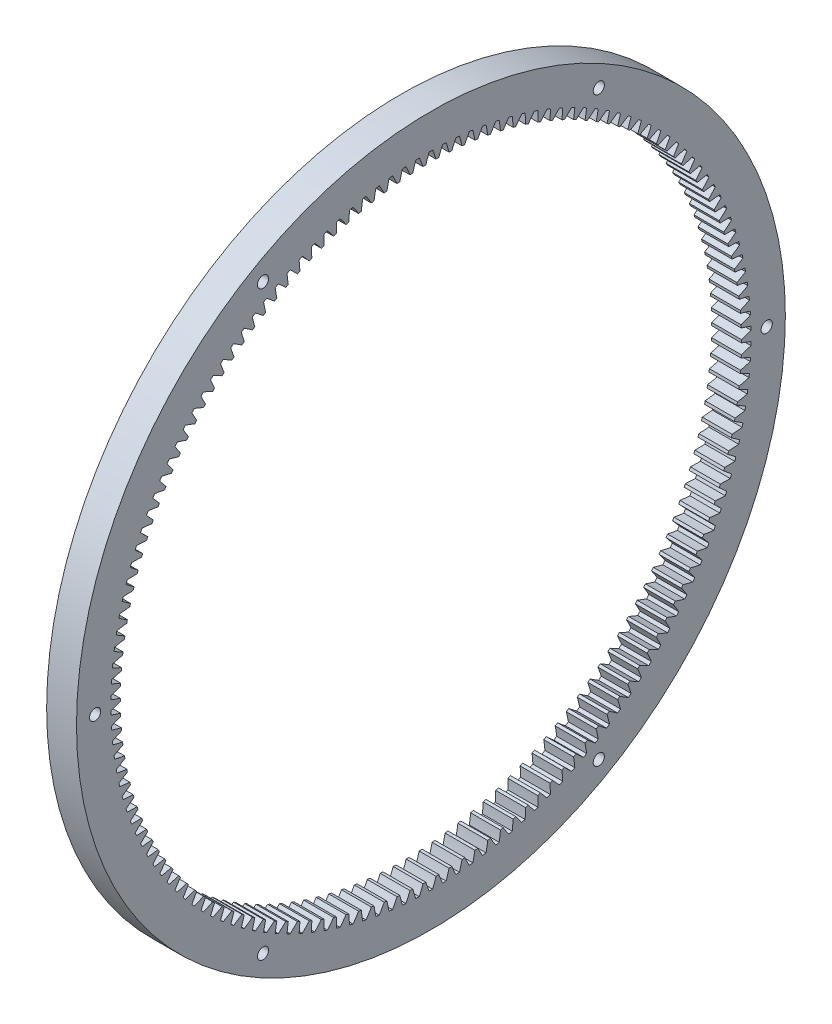
SolidWorks part; units mm, degrees
ref_plane "Plano frontal" through (0, 0, 0) normal (0, 0, 1) x (1, 0, 0)
ref_plane "Plano superior" through (0, 0, 0) normal (0, 1, 0) x (1, 0, 0)
ref_plane "Plano direito" through (0, 0, 0) normal (1, 0, 0) x (0, 0, -1)
ref_plane "Plano1" through (12, 0, 0) normal (1, 0, 0) x (0, 0, -1)
sketch "Esboço1" plane through (12, 0, 0) normal (1, 0, 0) x (0, 0, -1)
  circle A0 centre (-45, 77.9423) radius 1.5
  circle A1 centre (-90, 0) radius 1.5
  circle A2 centre (-45, -77.9423) radius 1.5
  circle A3 centre (45, -77.9423) radius 1.5
  circle A4 centre (90, 0) radius 1.5
  circle A5 centre (45, 77.9423) radius 1.5
  circle A6 centre (0, 0) radius 95
  arc A7 (2.1245, 83.2229) -> (3.1214, 85.7254) centre (41.7952, 68.8695) cw
  arc A8 (3.1214, 85.7254) -> (4.0628, 85.686) centre (0, 0) cw
  arc A9 (4.0628, 85.686) -> (4.8469, 83.1088) centre (-35.8858, 72.1253) cw
  arc A10 (4.8469, 83.1088) -> (5.6077, 83.0609) centre (0, 0) cw
  arc A11 (5.6077, 83.0609) -> (6.7085, 85.5195) centre (44.6425, 67.0589) cw
  arc A12 (6.7085, 85.5195) -> (7.6474, 85.4407) centre (0, 0) cw
  arc A13 (7.6474, 85.4407) -> (8.3228, 82.8329) centre (-32.834, 73.5647) cw
  arc A14 (8.3228, 82.8329) -> (9.081, 82.7532) centre (0, 0) cw
  arc A15 (9.081, 82.7532) -> (10.2838, 85.1636) centre (47.4115, 65.1306) cw
  arc A16 (10.2838, 85.1636) -> (11.2186, 85.0455) centre (0, 0) cw
  arc A17 (11.2186, 85.0455) -> (11.7842, 82.4117) centre (-29.7246, 74.8752) cw
  arc A18 (11.7842, 82.4117) -> (12.5383, 82.3004) centre (0, 0) cw
  arc A19 (12.5383, 82.3004) -> (13.8411, 84.6583) centre (50.0973, 63.0881) cw
  arc A20 (13.8411, 84.6583) -> (14.7701, 84.5011) centre (0, 0) cw
  arc A21 (14.7701, 84.5011) -> (15.2249, 81.846) centre (-26.5631, 76.0542) cw
  arc A22 (15.2249, 81.846) -> (15.9737, 81.7031) centre (0, 0) cw
  arc A23 (15.9737, 81.7031) -> (17.374, 84.0044) centre (52.6952, 60.9349) cw
  arc A24 (17.374, 84.0044) -> (18.2957, 83.8085) centre (0, 0) cw
  arc A25 (18.2957, 83.8085) -> (18.6389, 81.1366) centre (-23.355, 77.0998) cw
  arc A26 (18.6389, 81.1366) -> (19.3811, 80.9626) centre (0, 0) cw
  arc A27 (19.3811, 80.9626) -> (20.8765, 83.2032) centre (55.2006, 58.6748) cw
  arc A28 (20.8765, 83.2032) -> (21.7892, 82.9688) centre (0, 0) cw
  arc A29 (21.7892, 82.9688) -> (22.0202, 80.2849) centre (-20.1059, 78.0102) cw
  arc A30 (22.0202, 80.2849) -> (22.7544, 80.0799) centre (0, 0) cw
  arc A31 (22.7544, 80.0799) -> (24.3424, 82.256) centre (57.6093, 56.3118) cw
  arc A32 (24.3424, 82.256) -> (25.2444, 81.9836) centre (0, 0) cw
  arc A33 (25.2444, 81.9836) -> (25.3629, 79.2924) centre (-16.8215, 78.7837) cw
  arc A34 (25.3629, 79.2924) -> (26.0879, 79.0568) centre (0, 0) cw
  arc A35 (26.0879, 79.0568) -> (27.7656, 81.1644) centre (59.9168, 53.8499) cw
  arc A36 (27.7656, 81.1644) -> (28.6554, 80.8546) centre (0, 0) cw
  arc A37 (28.6554, 80.8546) -> (28.6611, 78.1608) centre (-13.5077, 79.419) cw
  arc A38 (28.6611, 78.1608) -> (29.3756, 77.895) centre (0, 0) cw
  arc A39 (29.3756, 77.895) -> (31.14, 79.9305) centre (62.1193, 51.2936) cw
  arc A40 (31.14, 79.9305) -> (32.0161, 79.5837) centre (0, 0) cw
  arc A41 (32.0161, 79.5837) -> (31.909, 76.892) centre (-10.1701, 79.915) cw
  arc A42 (31.909, 76.892) -> (32.6117, 76.5966) centre (0, 0) cw
  arc A43 (32.6117, 76.5966) -> (34.4599, 78.5564) centre (64.2127, 48.6474) cw
  arc A44 (34.4599, 78.5564) -> (35.3207, 78.1732) centre (0, 0) cw
  arc A45 (35.3207, 78.1732) -> (35.1009, 75.4883) centre (-6.8147, 80.2708) cw
  arc A46 (35.1009, 75.4883) -> (35.7906, 75.1638) centre (0, 0) cw
  arc A47 (35.7906, 75.1638) -> (37.7192, 77.0445) centre (66.1936, 45.9157) cw
  arc A48 (37.7192, 77.0445) -> (38.5632, 76.6255) centre (0, 0) cw
  arc A49 (38.5632, 76.6255) -> (38.2312, 73.9523) centre (-3.4473, 80.4858) cw
  arc A50 (38.2312, 73.9523) -> (38.9068, 73.5991) centre (0, 0) cw
  arc A51 (38.9068, 73.5991) -> (40.9124, 75.3974) centre (68.0582, 43.1036) cw
  arc A52 (40.9124, 75.3974) -> (41.7381, 74.9435) centre (0, 0) cw
  arc A53 (41.7381, 74.9435) -> (41.2945, 72.2864) centre (-0.0739, 80.5595) cw
  arc A54 (41.2945, 72.2864) -> (41.9546, 71.9053) centre (0, 0) cw
  arc A55 (41.9546, 71.9053) -> (44.0339, 73.618) centre (69.8035, 40.2158) cw
  arc A56 (44.0339, 73.618) -> (44.8398, 73.1299) centre (0, 0) cw
  arc A57 (44.8398, 73.1299) -> (44.2853, 70.4938) centre (3.2997, 80.492) cw
  arc A58 (44.2853, 70.4938) -> (44.9289, 70.0853) centre (0, 0) cw
  arc A59 (44.9289, 70.0853) -> (47.078, 71.7095) centre (71.4264, 37.2574) cw
  arc A60 (47.078, 71.7095) -> (47.8629, 71.1881) centre (0, 0) cw
  arc A61 (47.8629, 71.1881) -> (47.1984, 68.5775) centre (6.6674, 80.2832) cw
  arc A62 (47.1984, 68.5775) -> (47.8244, 68.1424) centre (0, 0) cw
  arc A63 (47.8244, 68.1424) -> (50.0396, 69.6752) centre (72.9239, 34.2337) cw
  arc A64 (50.0396, 69.6752) -> (50.8019, 69.1213) centre (0, 0) cw
  arc A65 (50.8019, 69.1213) -> (50.0288, 66.5409) centre (10.0235, 79.9335) cw
  arc A66 (50.0288, 66.5409) -> (50.6359, 66.08) centre (0, 0) cw
  arc A67 (50.6359, 66.08) -> (52.9134, 67.5186) centre (74.2935, 31.15) cw
  arc A68 (52.9134, 67.5186) -> (53.6519, 66.9333) centre (0, 0) cw
  arc A69 (53.6519, 66.9333) -> (52.7713, 64.3875) centre (13.362, 79.4437) cw
  arc A70 (52.7713, 64.3875) -> (53.3587, 63.9016) centre (0, 0) cw
  arc A71 (53.3587, 63.9016) -> (55.6944, 65.2436) centre (75.5327, 28.0116) cw
  arc A72 (55.6944, 65.2436) -> (56.4077, 64.6279) centre (0, 0) cw
  arc A73 (56.4077, 64.6279) -> (55.4213, 62.1212) centre (16.677, 78.8145) cw
  arc A74 (55.4213, 62.1212) -> (55.9878, 61.6111) centre (0, 0) cw
  arc A75 (55.9878, 61.6111) -> (58.3777, 62.8541) centre (76.6395, 24.824) cw
  arc A76 (58.3777, 62.8541) -> (59.0645, 62.2091) centre (0, 0) cw
  arc A77 (59.0645, 62.2091) -> (57.974, 59.7459) centre (19.9628, 78.047) cw
  arc A78 (57.974, 59.7459) -> (58.5187, 59.2126) centre (0, 0) cw
  arc A79 (58.5187, 59.2126) -> (60.9585, 60.3544) centre (77.6118, 21.5929) cw
  arc A80 (60.9585, 60.3544) -> (61.6178, 59.6812) centre (0, 0) cw
  arc A81 (61.6178, 59.6812) -> (60.4251, 57.2658) centre (23.2135, 77.1426) cw
  arc A82 (60.4251, 57.2658) -> (60.9469, 56.7101) centre (0, 0) cw
  arc A83 (60.9469, 56.7101) -> (63.4324, 57.7488) centre (78.4479, 18.3239) cw
  arc A84 (63.4324, 57.7488) -> (64.0629, 57.0486) centre (0, 0) cw
  arc A85 (64.0629, 57.0486) -> (62.7701, 54.6852) centre (26.4236, 76.1028) cw
  arc A86 (62.7701, 54.6852) -> (63.2682, 54.1082) centre (0, 0) cw
  arc A87 (63.2682, 54.1082) -> (65.7951, 55.0418) centre (79.1464, 15.0228) cw
  arc A88 (65.7951, 55.0418) -> (66.3957, 54.3158) centre (0, 0) cw
  arc A89 (66.3957, 54.3158) -> (65.005, 52.0087) centre (29.5872, 74.9295) cw
  arc A90 (65.005, 52.0087) -> (65.4785, 51.4113) centre (0, 0) cw
  arc A91 (65.4785, 51.4113) -> (68.0423, 52.2384) centre (79.7061, 11.6953) cw
  arc A92 (68.0423, 52.2384) -> (68.6119, 51.4878) centre (0, 0) cw
  arc A93 (68.6119, 51.4878) -> (67.1259, 49.241) centre (32.699, 73.6248) cw
  arc A94 (67.1259, 49.241) -> (67.574, 48.6243) centre (0, 0) cw
  arc A95 (67.574, 48.6243) -> (70.1701, 49.3432) centre (80.1259, 8.3473) cw
  arc A96 (70.1701, 49.3432) -> (70.7078, 48.5695) centre (0, 0) cw
  arc A97 (70.7078, 48.5695) -> (69.129, 46.3868) centre (35.7534, 72.191) cw
  arc A98 (69.129, 46.3868) -> (69.5509, 45.7519) centre (0, 0) cw
  arc A99 (69.5509, 45.7519) -> (72.1748, 46.3615) centre (80.4052, 4.9846) cw
  arc A100 (72.1748, 46.3615) -> (72.6797, 45.566) centre (0, 0) cw
  arc A101 (72.6797, 45.566) -> (71.0109, 43.4513) centre (38.7451, 70.6304) cw
  arc A102 (71.0109, 43.4513) -> (71.4058, 42.7993) centre (0, 0) cw
  arc A103 (71.4058, 42.7993) -> (74.0529, 43.2985) centre (80.5434, 1.6132) cw
  arc A104 (74.0529, 43.2985) -> (74.524, 42.4825) centre (0, 0) cw
  arc A105 (74.524, 42.4825) -> (72.7681, 40.4396) centre (41.6688, 68.946) cw
  arc A106 (72.7681, 40.4396) -> (73.1354, 39.7716) centre (0, 0) cw
  arc A107 (73.1354, 39.7716) -> (75.8011, 40.1595) centre (80.5403, -1.761) cw
  arc A108 (75.8011, 40.1595) -> (76.2377, 39.3245) centre (0, 0) cw
  arc A109 (76.2377, 39.3245) -> (74.3977, 37.3569) centre (44.5194, 67.1406) cw
  arc A110 (74.3977, 37.3569) -> (74.7367, 36.6741) centre (0, 0) cw
  arc A111 (74.7367, 36.6741) -> (77.4163, 36.95) centre (80.3959, -5.1321) cw
  arc A112 (77.4163, 36.95) -> (77.8175, 36.0975) centre (0, 0) cw
  arc A113 (77.8175, 36.0975) -> (75.8968, 34.2087) centre (47.2919, 65.2174) cw
  arc A114 (75.8968, 34.2087) -> (76.2069, 33.5123) centre (0, 0) cw
  arc A115 (76.2069, 33.5123) -> (78.8957, 33.6758) centre (80.1105, -8.4942) cw
  arc A116 (78.8957, 33.6758) -> (79.2609, 32.8071) centre (0, 0) cw
  arc A117 (79.2609, 32.8071) -> (77.2628, 31.0004) centre (49.9815, 63.1799) cw
  arc A118 (77.2628, 31.0004) -> (77.5434, 30.2917) centre (0, 0) cw
  arc A119 (77.5434, 30.2917) -> (80.2367, 30.3424) centre (79.6845, -11.8415) cw
  arc A120 (80.2367, 30.3424) -> (80.5652, 29.4593) centre (0, 0) cw
  arc A121 (80.5652, 29.4593) -> (78.4932, 27.7378) centre (52.5833, 61.0314) cw
  arc A122 (78.4932, 27.7378) -> (78.7439, 27.0179) centre (0, 0) cw
  arc A123 (78.7439, 27.0179) -> (81.437, 26.9558) centre (79.1187, -15.1679) cw
  arc A124 (81.437, 26.9558) -> (81.7281, 26.0597) centre (0, 0) cw
  arc A125 (81.7281, 26.0597) -> (79.5858, 24.4265) centre (55.0929, 58.7759) cw
  arc A126 (79.5858, 24.4265) -> (79.8062, 23.6968) centre (0, 0) cw
  arc A127 (79.8062, 23.6968) -> (82.4943, 23.522) centre (78.4142, -18.4678) cw
  arc A128 (82.4943, 23.522) -> (82.7477, 22.6144) centre (0, 0) cw
  arc A129 (82.7477, 22.6144) -> (80.5389, 21.0724) centre (57.5059, 56.4173) cw
  arc A130 (80.5389, 21.0724) -> (80.7285, 20.334) centre (0, 0) cw
  arc A131 (80.7285, 20.334) -> (83.4069, 20.0468) centre (77.572, -21.7352) cw
  arc A132 (83.4069, 20.0468) -> (83.6221, 19.1295) centre (0, 0) cw
  arc A133 (83.6221, 19.1295) -> (81.3507, 17.6813) centre (59.818, 53.9597) cw
  arc A134 (81.3507, 17.6813) -> (81.5092, 16.9356) centre (0, 0) cw
  arc A135 (81.5092, 16.9356) -> (84.1733, 16.5365) centre (76.5938, -24.9645) cw
  arc A136 (84.1733, 16.5365) -> (84.3498, 15.611) centre (0, 0) cw
  arc A137 (84.3498, 15.611) -> (82.0197, 14.2592) centre (62.0251, 51.4075) cw
  arc A138 (82.0197, 14.2592) -> (82.1469, 13.5075) centre (0, 0) cw
  arc A139 (82.1469, 13.5075) -> (84.7919, 12.9972) centre (75.4812, -28.15) cw
  arc A140 (84.7919, 12.9972) -> (84.9295, 12.0651) centre (0, 0) cw
  arc A141 (84.9295, 12.0651) -> (82.5449, 10.812) centre (64.1234, 48.7651) cw
  arc A142 (82.5449, 10.812) -> (82.6405, 10.0557) centre (0, 0) cw
  arc A143 (82.6405, 10.0557) -> (85.2618, 9.4351) centre (74.2362, -31.2862) cw
  arc A144 (85.2618, 9.4351) -> (85.3603, 8.498) centre (0, 0) cw
  arc A145 (85.3603, 8.498) -> (82.9253, 7.3459) centre (66.1092, 46.0371) cw
  arc A146 (82.9253, 7.3459) -> (82.9891, 6.5863) centre (0, 0) cw
  arc A147 (82.9891, 6.5863) -> (85.5821, 5.8564) centre (72.861, -34.3674) cw
  arc A148 (85.5821, 5.8564) -> (85.6413, 4.916) centre (0, 0) cw
  arc A149 (85.6413, 4.916) -> (83.1601, 3.8669) centre (67.9791, 43.2283) cw
  arc A150 (83.1601, 3.8669) -> (83.1921, 3.1053) centre (0, 0) cw
  arc A151 (83.1921, 3.1053) -> (85.7523, 2.2675) centre (71.3579, -37.3884) cw
  arc A152 (85.7523, 2.2675) -> (85.772, 1.3254) centre (0, 0) cw
  arc A153 (85.772, 1.3254) -> (83.2491, 0.3811) centre (69.7297, 40.3437) cw
  arc A154 (83.2491, 0.3811) -> (83.2491, -0.3811) centre (0, 0) cw
  arc A155 (83.2491, -0.3811) -> (85.772, -1.3254) centre (69.7297, -40.3437) cw
  arc A156 (85.772, -1.3254) -> (85.7523, -2.2675) centre (0, 0) cw
  arc A157 (85.7523, -2.2675) -> (83.1921, -3.1053) centre (71.3579, 37.3884) cw
  arc A158 (83.1921, -3.1053) -> (83.1601, -3.8669) centre (0, 0) cw
  arc A159 (83.1601, -3.8669) -> (85.6413, -4.916) centre (67.9791, -43.2283) cw
  arc A160 (85.6413, -4.916) -> (85.5821, -5.8564) centre (0, 0) cw
  arc A161 (85.5821, -5.8564) -> (82.9891, -6.5863) centre (72.861, 34.3674) cw
  arc A162 (82.9891, -6.5863) -> (82.9253, -7.3459) centre (0, 0) cw
  arc A163 (82.9253, -7.3459) -> (85.3603, -8.498) centre (66.1092, -46.0371) cw
  arc A164 (85.3603, -8.498) -> (85.2618, -9.4351) centre (0, 0) cw
  arc A165 (85.2618, -9.4351) -> (82.6405, -10.0557) centre (74.2362, 31.2862) cw
  arc A166 (82.6405, -10.0557) -> (82.5449, -10.812) centre (0, 0) cw
  arc A167 (82.5449, -10.812) -> (84.9295, -12.0651) centre (64.1234, -48.7651) cw
  arc A168 (84.9295, -12.0651) -> (84.7919, -12.9972) centre (0, 0) cw
  arc A169 (84.7919, -12.9972) -> (82.1469, -13.5075) centre (75.4812, 28.15) cw
  arc A170 (82.1469, -13.5075) -> (82.0197, -14.2592) centre (0, 0) cw
  arc A171 (82.0197, -14.2592) -> (84.3498, -15.611) centre (62.0251, -51.4075) cw
  arc A172 (84.3498, -15.611) -> (84.1733, -16.5365) centre (0, 0) cw
  arc A173 (84.1733, -16.5365) -> (81.5092, -16.9356) centre (76.5938, 24.9645) cw
  arc A174 (81.5092, -16.9356) -> (81.3507, -17.6813) centre (0, 0) cw
  arc A175 (81.3507, -17.6813) -> (83.6221, -19.1295) centre (59.818, -53.9597) cw
  arc A176 (83.6221, -19.1295) -> (83.4069, -20.0468) centre (0, 0) cw
  arc A177 (83.4069, -20.0468) -> (80.7285, -20.334) centre (77.572, 21.7352) cw
  arc A178 (80.7285, -20.334) -> (80.5389, -21.0724) centre (0, 0) cw
  arc A179 (80.5389, -21.0724) -> (82.7477, -22.6144) centre (57.5059, -56.4173) cw
  arc A180 (82.7477, -22.6144) -> (82.4943, -23.522) centre (0, 0) cw
  arc A181 (82.4943, -23.522) -> (79.8062, -23.6968) centre (78.4142, 18.4678) cw
  arc A182 (79.8062, -23.6968) -> (79.5858, -24.4265) centre (0, 0) cw
  arc A183 (79.5858, -24.4265) -> (81.7281, -26.0597) centre (55.0929, -58.7759) cw
  arc A184 (81.7281, -26.0597) -> (81.437, -26.9558) centre (0, 0) cw
  arc A185 (81.437, -26.9558) -> (78.7439, -27.0179) centre (79.1187, 15.1679) cw
  arc A186 (78.7439, -27.0179) -> (78.4932, -27.7378) centre (0, 0) cw
  arc A187 (78.4932, -27.7378) -> (80.5652, -29.4593) centre (52.5833, -61.0314) cw
  arc A188 (80.5652, -29.4593) -> (80.2367, -30.3424) centre (0, 0) cw
  arc A189 (80.2367, -30.3424) -> (77.5434, -30.2917) centre (79.6845, 11.8415) cw
  arc A190 (77.5434, -30.2917) -> (77.2628, -31.0004) centre (0, 0) cw
  arc A191 (77.2628, -31.0004) -> (79.2609, -32.8071) centre (49.9815, -63.1799) cw
  arc A192 (79.2609, -32.8071) -> (78.8957, -33.6758) centre (0, 0) cw
  arc A193 (78.8957, -33.6758) -> (76.2069, -33.5123) centre (80.1105, 8.4942) cw
  arc A194 (76.2069, -33.5123) -> (75.8968, -34.2087) centre (0, 0) cw
  arc A195 (75.8968, -34.2087) -> (77.8175, -36.0975) centre (47.2919, -65.2174) cw
  arc A196 (77.8175, -36.0975) -> (77.4163, -36.95) centre (0, 0) cw
  arc A197 (77.4163, -36.95) -> (74.7367, -36.6741) centre (80.3959, 5.1321) cw
  arc A198 (74.7367, -36.6741) -> (74.3977, -37.3569) centre (0, 0) cw
  arc A199 (74.3977, -37.3569) -> (76.2377, -39.3245) centre (44.5194, -67.1406) cw
  arc A200 (76.2377, -39.3245) -> (75.8011, -40.1595) centre (0, 0) cw
  arc A201 (75.8011, -40.1595) -> (73.1354, -39.7716) centre (80.5403, 1.761) cw
  arc A202 (73.1354, -39.7716) -> (72.7681, -40.4396) centre (0, 0) cw
  arc A203 (72.7681, -40.4396) -> (74.524, -42.4825) centre (41.6688, -68.946) cw
  arc A204 (74.524, -42.4825) -> (74.0529, -43.2985) centre (0, 0) cw
  arc A205 (74.0529, -43.2985) -> (71.4058, -42.7993) centre (80.5434, -1.6132) cw
  arc A206 (71.4058, -42.7993) -> (71.0109, -43.4513) centre (0, 0) cw
  arc A207 (71.0109, -43.4513) -> (72.6797, -45.566) centre (38.7451, -70.6304) cw
  arc A208 (72.6797, -45.566) -> (72.1748, -46.3615) centre (0, 0) cw
  arc A209 (72.1748, -46.3615) -> (69.5509, -45.7519) centre (80.4052, -4.9846) cw
  arc A210 (69.5509, -45.7519) -> (69.129, -46.3868) centre (0, 0) cw
  arc A211 (69.129, -46.3868) -> (70.7078, -48.5695) centre (35.7534, -72.191) cw
  arc A212 (70.7078, -48.5695) -> (70.1701, -49.3432) centre (0, 0) cw
  arc A213 (70.1701, -49.3432) -> (67.574, -48.6243) centre (80.1259, -8.3473) cw
  arc A214 (67.574, -48.6243) -> (67.1259, -49.241) centre (0, 0) cw
  arc A215 (67.1259, -49.241) -> (68.6119, -51.4878) centre (32.699, -73.6248) cw
  arc A216 (68.6119, -51.4878) -> (68.0423, -52.2384) centre (0, 0) cw
  arc A217 (68.0423, -52.2384) -> (65.4785, -51.4113) centre (79.7061, -11.6953) cw
  arc A218 (65.4785, -51.4113) -> (65.005, -52.0087) centre (0, 0) cw
  arc A219 (65.005, -52.0087) -> (66.3957, -54.3158) centre (29.5872, -74.9295) cw
  arc A220 (66.3957, -54.3158) -> (65.7951, -55.0418) centre (0, 0) cw
  arc A221 (65.7951, -55.0418) -> (63.2682, -54.1082) centre (79.1464, -15.0228) cw
  arc A222 (63.2682, -54.1082) -> (62.7701, -54.6852) centre (0, 0) cw
  arc A223 (62.7701, -54.6852) -> (64.0629, -57.0486) centre (26.4236, -76.1028) cw
  arc A224 (64.0629, -57.0486) -> (63.4324, -57.7488) centre (0, 0) cw
  arc A225 (63.4324, -57.7488) -> (60.9469, -56.7101) centre (78.4479, -18.3239) cw
  arc A226 (60.9469, -56.7101) -> (60.4251, -57.2658) centre (0, 0) cw
  arc A227 (60.4251, -57.2658) -> (61.6178, -59.6812) centre (23.2135, -77.1426) cw
  arc A228 (61.6178, -59.6812) -> (60.9585, -60.3544) centre (0, 0) cw
  arc A229 (60.9585, -60.3544) -> (58.5187, -59.2126) centre (77.6118, -21.5929) cw
  arc A230 (58.5187, -59.2126) -> (57.974, -59.7459) centre (0, 0) cw
  arc A231 (57.974, -59.7459) -> (59.0645, -62.2091) centre (19.9628, -78.047) cw
  arc A232 (59.0645, -62.2091) -> (58.3777, -62.8541) centre (0, 0) cw
  arc A233 (58.3777, -62.8541) -> (55.9878, -61.6111) centre (76.6395, -24.824) cw
  arc A234 (55.9878, -61.6111) -> (55.4213, -62.1212) centre (0, 0) cw
  arc A235 (55.4213, -62.1212) -> (56.4077, -64.6279) centre (16.677, -78.8145) cw
  arc A236 (56.4077, -64.6279) -> (55.6944, -65.2436) centre (0, 0) cw
  arc A237 (55.6944, -65.2436) -> (53.3587, -63.9016) centre (75.5327, -28.0116) cw
  arc A238 (53.3587, -63.9016) -> (52.7713, -64.3875) centre (0, 0) cw
  arc A239 (52.7713, -64.3875) -> (53.6519, -66.9333) centre (13.362, -79.4437) cw
  arc A240 (53.6519, -66.9333) -> (52.9134, -67.5186) centre (0, 0) cw
  arc A241 (52.9134, -67.5186) -> (50.6359, -66.08) centre (74.2935, -31.15) cw
  arc A242 (50.6359, -66.08) -> (50.0288, -66.5409) centre (0, 0) cw
  arc A243 (50.0288, -66.5409) -> (50.8019, -69.1213) centre (10.0235, -79.9335) cw
  arc A244 (50.8019, -69.1213) -> (50.0396, -69.6752) centre (0, 0) cw
  arc A245 (50.0396, -69.6752) -> (47.8244, -68.1424) centre (72.9239, -34.2337) cw
  arc A246 (47.8244, -68.1424) -> (47.1984, -68.5775) centre (0, 0) cw
  arc A247 (47.1984, -68.5775) -> (47.8629, -71.1881) centre (6.6674, -80.2832) cw
  arc A248 (47.8629, -71.1881) -> (47.078, -71.7095) centre (0, 0) cw
  arc A249 (47.078, -71.7095) -> (44.9289, -70.0853) centre (71.4264, -37.2574) cw
  arc A250 (44.9289, -70.0853) -> (44.2853, -70.4938) centre (0, 0) cw
  arc A251 (44.2853, -70.4938) -> (44.8398, -73.1299) centre (3.2997, -80.492) cw
  arc A252 (44.8398, -73.1299) -> (44.0339, -73.618) centre (0, 0) cw
  arc A253 (44.0339, -73.618) -> (41.9546, -71.9053) centre (69.8035, -40.2158) cw
  arc A254 (41.9546, -71.9053) -> (41.2945, -72.2864) centre (0, 0) cw
  arc A255 (41.2945, -72.2864) -> (41.7381, -74.9435) centre (-0.0739, -80.5595) cw
  arc A256 (41.7381, -74.9435) -> (40.9124, -75.3974) centre (0, 0) cw
  arc A257 (40.9124, -75.3974) -> (38.9068, -73.5991) centre (68.0582, -43.1036) cw
  arc A258 (38.9068, -73.5991) -> (38.2312, -73.9523) centre (0, 0) cw
  arc A259 (38.2312, -73.9523) -> (38.5632, -76.6255) centre (-3.4473, -80.4858) cw
  arc A260 (38.5632, -76.6255) -> (37.7192, -77.0445) centre (0, 0) cw
  arc A261 (37.7192, -77.0445) -> (35.7906, -75.1638) centre (66.1936, -45.9157) cw
  arc A262 (35.7906, -75.1638) -> (35.1009, -75.4883) centre (0, 0) cw
  arc A263 (35.1009, -75.4883) -> (35.3207, -78.1732) centre (-6.8147, -80.2708) cw
  arc A264 (35.3207, -78.1732) -> (34.4599, -78.5564) centre (0, 0) cw
  arc A265 (34.4599, -78.5564) -> (32.6117, -76.5966) centre (64.2127, -48.6474) cw
  arc A266 (32.6117, -76.5966) -> (31.909, -76.892) centre (0, 0) cw
  arc A267 (31.909, -76.892) -> (32.0161, -79.5837) centre (-10.1701, -79.915) cw
  arc A268 (32.0161, -79.5837) -> (31.14, -79.9305) centre (0, 0) cw
  arc A269 (31.14, -79.9305) -> (29.3756, -77.895) centre (62.1193, -51.2936) cw
  arc A270 (29.3756, -77.895) -> (28.6611, -78.1608) centre (0, 0) cw
  arc A271 (28.6611, -78.1608) -> (28.6554, -80.8546) centre (-13.5077, -79.419) cw
  arc A272 (28.6554, -80.8546) -> (27.7656, -81.1644) centre (0, 0) cw
  arc A273 (27.7656, -81.1644) -> (26.0879, -79.0568) centre (59.9168, -53.8499) cw
  arc A274 (26.0879, -79.0568) -> (25.3629, -79.2924) centre (0, 0) cw
  arc A275 (25.3629, -79.2924) -> (25.2444, -81.9836) centre (-16.8215, -78.7837) cw
  arc A276 (25.2444, -81.9836) -> (24.3424, -82.256) centre (0, 0) cw
  arc A277 (24.3424, -82.256) -> (22.7544, -80.0799) centre (57.6093, -56.3118) cw
  arc A278 (22.7544, -80.0799) -> (22.0202, -80.2849) centre (0, 0) cw
  arc A279 (22.0202, -80.2849) -> (21.7892, -82.9688) centre (-20.1059, -78.0102) cw
  arc A280 (21.7892, -82.9688) -> (20.8765, -83.2032) centre (0, 0) cw
  arc A281 (20.8765, -83.2032) -> (19.3811, -80.9626) centre (55.2006, -58.6748) cw
  arc A282 (19.3811, -80.9626) -> (18.6389, -81.1366) centre (0, 0) cw
  arc A283 (18.6389, -81.1366) -> (18.2957, -83.8085) centre (-23.355, -77.0998) cw
  arc A284 (18.2957, -83.8085) -> (17.374, -84.0044) centre (0, 0) cw
  arc A285 (17.374, -84.0044) -> (15.9737, -81.7031) centre (52.6952, -60.9349) cw
  arc A286 (15.9737, -81.7031) -> (15.2249, -81.846) centre (0, 0) cw
  arc A287 (15.2249, -81.846) -> (14.7701, -84.5011) centre (-26.5631, -76.0542) cw
  arc A288 (14.7701, -84.5011) -> (13.8411, -84.6583) centre (0, 0) cw
  arc A289 (13.8411, -84.6583) -> (12.5383, -82.3004) centre (50.0973, -63.0881) cw
  arc A290 (12.5383, -82.3004) -> (11.7842, -82.4117) centre (0, 0) cw
  arc A291 (11.7842, -82.4117) -> (11.2186, -85.0455) centre (-29.7246, -74.8752) cw
  arc A292 (11.2186, -85.0455) -> (10.2838, -85.1636) centre (0, 0) cw
  arc A293 (10.2838, -85.1636) -> (9.081, -82.7532) centre (47.4115, -65.1306) cw
  arc A294 (9.081, -82.7532) -> (8.3228, -82.8329) centre (0, 0) cw
  arc A295 (8.3228, -82.8329) -> (7.6474, -85.4407) centre (-32.834, -73.5647) cw
  arc A296 (7.6474, -85.4407) -> (6.7085, -85.5195) centre (0, 0) cw
  arc A297 (6.7085, -85.5195) -> (5.6077, -83.0609) centre (44.6425, -67.0589) cw
  arc A298 (5.6077, -83.0609) -> (4.8469, -83.1088) centre (0, 0) cw
  arc A299 (4.8469, -83.1088) -> (4.0628, -85.686) centre (-35.8858, -72.1253) cw
  arc A300 (4.0628, -85.686) -> (3.1214, -85.7254) centre (0, 0) cw
  arc A301 (3.1214, -85.7254) -> (2.1245, -83.2229) centre (41.7952, -68.8695) cw
  arc A302 (2.1245, -83.2229) -> (1.3624, -83.2389) centre (0, 0) cw
  arc A303 (1.3624, -83.2389) -> (0.4711, -85.781) centre (-38.8746, -70.5593) cw
  arc A304 (0.4711, -85.781) -> (-0.4711, -85.781) centre (0, 0) cw
  arc A305 (-0.4711, -85.781) -> (-1.3624, -83.2389) centre (38.8746, -70.5593) cw
  arc A306 (-1.3624, -83.2389) -> (-2.1245, -83.2229) centre (0, 0) cw
  arc A307 (-2.1245, -83.2229) -> (-3.1214, -85.7254) centre (-41.7952, -68.8695) cw
  arc A308 (-3.1214, -85.7254) -> (-4.0628, -85.686) centre (0, 0) cw
  arc A309 (-4.0628, -85.686) -> (-4.8469, -83.1088) centre (35.8858, -72.1253) cw
  arc A310 (-4.8469, -83.1088) -> (-5.6077, -83.0609) centre (0, 0) cw
  arc A311 (-5.6077, -83.0609) -> (-6.7085, -85.5195) centre (-44.6425, -67.0589) cw
  arc A312 (-6.7085, -85.5195) -> (-7.6474, -85.4407) centre (0, 0) cw
  arc A313 (-7.6474, -85.4407) -> (-8.3228, -82.8329) centre (32.834, -73.5647) cw
  arc A314 (-8.3228, -82.8329) -> (-9.081, -82.7532) centre (0, 0) cw
  arc A315 (-9.081, -82.7532) -> (-10.2838, -85.1636) centre (-47.4115, -65.1306) cw
  arc A316 (-10.2838, -85.1636) -> (-11.2186, -85.0455) centre (0, 0) cw
  arc A317 (-11.2186, -85.0455) -> (-11.7842, -82.4117) centre (29.7246, -74.8752) cw
  arc A318 (-11.7842, -82.4117) -> (-12.5383, -82.3004) centre (0, 0) cw
  arc A319 (-12.5383, -82.3004) -> (-13.8411, -84.6583) centre (-50.0973, -63.0881) cw
  arc A320 (-13.8411, -84.6583) -> (-14.7701, -84.5011) centre (0, 0) cw
  arc A321 (-14.7701, -84.5011) -> (-15.2249, -81.846) centre (26.5631, -76.0542) cw
  arc A322 (-15.2249, -81.846) -> (-15.9737, -81.7031) centre (0, 0) cw
  arc A323 (-15.9737, -81.7031) -> (-17.374, -84.0044) centre (-52.6952, -60.9349) cw
  arc A324 (-17.374, -84.0044) -> (-18.2957, -83.8085) centre (0, 0) cw
  arc A325 (-18.2957, -83.8085) -> (-18.6389, -81.1366) centre (23.355, -77.0998) cw
  arc A326 (-18.6389, -81.1366) -> (-19.3811, -80.9626) centre (0, 0) cw
  arc A327 (-19.3811, -80.9626) -> (-20.8765, -83.2032) centre (-55.2006, -58.6748) cw
  arc A328 (-20.8765, -83.2032) -> (-21.7892, -82.9688) centre (0, 0) cw
  arc A329 (-21.7892, -82.9688) -> (-22.0202, -80.2849) centre (20.1059, -78.0102) cw
  arc A330 (-22.0202, -80.2849) -> (-22.7544, -80.0799) centre (0, 0) cw
  arc A331 (-22.7544, -80.0799) -> (-24.3424, -82.256) centre (-57.6093, -56.3118) cw
  arc A332 (-24.3424, -82.256) -> (-25.2444, -81.9836) centre (0, 0) cw
  arc A333 (-25.2444, -81.9836) -> (-25.3629, -79.2924) centre (16.8215, -78.7837) cw
  arc A334 (-25.3629, -79.2924) -> (-26.0879, -79.0568) centre (0, 0) cw
  arc A335 (-26.0879, -79.0568) -> (-27.7656, -81.1644) centre (-59.9168, -53.8499) cw
  arc A336 (-27.7656, -81.1644) -> (-28.6554, -80.8546) centre (0, 0) cw
  arc A337 (-28.6554, -80.8546) -> (-28.6611, -78.1608) centre (13.5077, -79.419) cw
  arc A338 (-28.6611, -78.1608) -> (-29.3756, -77.895) centre (0, 0) cw
  arc A339 (-29.3756, -77.895) -> (-31.14, -79.9305) centre (-62.1193, -51.2936) cw
  arc A340 (-31.14, -79.9305) -> (-32.0161, -79.5837) centre (0, 0) cw
  arc A341 (-32.0161, -79.5837) -> (-31.909, -76.892) centre (10.1701, -79.915) cw
  arc A342 (-31.909, -76.892) -> (-32.6117, -76.5966) centre (0, 0) cw
  arc A343 (-32.6117, -76.5966) -> (-34.4599, -78.5564) centre (-64.2127, -48.6474) cw
  arc A344 (-34.4599, -78.5564) -> (-35.3207, -78.1732) centre (0, 0) cw
  arc A345 (-35.3207, -78.1732) -> (-35.1009, -75.4883) centre (6.8147, -80.2708) cw
  arc A346 (-35.1009, -75.4883) -> (-35.7906, -75.1638) centre (0, 0) cw
  arc A347 (-35.7906, -75.1638) -> (-37.7192, -77.0445) centre (-66.1936, -45.9157) cw
  arc A348 (-37.7192, -77.0445) -> (-38.5632, -76.6255) centre (0, 0) cw
  arc A349 (-38.5632, -76.6255) -> (-38.2312, -73.9523) centre (3.4473, -80.4858) cw
  arc A350 (-38.2312, -73.9523) -> (-38.9068, -73.5991) centre (0, 0) cw
  arc A351 (-38.9068, -73.5991) -> (-40.9124, -75.3974) centre (-68.0582, -43.1036) cw
  arc A352 (-40.9124, -75.3974) -> (-41.7381, -74.9435) centre (0, 0) cw
  arc A353 (-41.7381, -74.9435) -> (-41.2945, -72.2864) centre (0.0739, -80.5595) cw
  arc A354 (-41.2945, -72.2864) -> (-41.9546, -71.9053) centre (0, 0) cw
  arc A355 (-41.9546, -71.9053) -> (-44.0339, -73.618) centre (-69.8035, -40.2158) cw
  arc A356 (-44.0339, -73.618) -> (-44.8398, -73.1299) centre (0, 0) cw
  arc A357 (-44.8398, -73.1299) -> (-44.2853, -70.4938) centre (-3.2997, -80.492) cw
  arc A358 (-44.2853, -70.4938) -> (-44.9289, -70.0853) centre (0, 0) cw
  arc A359 (-44.9289, -70.0853) -> (-47.078, -71.7095) centre (-71.4264, -37.2574) cw
  arc A360 (-47.078, -71.7095) -> (-47.8629, -71.1881) centre (0, 0) cw
  arc A361 (-47.8629, -71.1881) -> (-47.1984, -68.5775) centre (-6.6674, -80.2832) cw
  arc A362 (-47.1984, -68.5775) -> (-47.8244, -68.1424) centre (0, 0) cw
  arc A363 (-47.8244, -68.1424) -> (-50.0396, -69.6752) centre (-72.9239, -34.2337) cw
  arc A364 (-50.0396, -69.6752) -> (-50.8019, -69.1213) centre (0, 0) cw
  arc A365 (-50.8019, -69.1213) -> (-50.0288, -66.5409) centre (-10.0235, -79.9335) cw
  arc A366 (-50.0288, -66.5409) -> (-50.6359, -66.08) centre (0, 0) cw
  arc A367 (-50.6359, -66.08) -> (-52.9134, -67.5186) centre (-74.2935, -31.15) cw
  arc A368 (-52.9134, -67.5186) -> (-53.6519, -66.9333) centre (0, 0) cw
  arc A369 (-53.6519, -66.9333) -> (-52.7713, -64.3875) centre (-13.362, -79.4437) cw
  arc A370 (-52.7713, -64.3875) -> (-53.3587, -63.9016) centre (0, 0) cw
  arc A371 (-53.3587, -63.9016) -> (-55.6944, -65.2436) centre (-75.5327, -28.0116) cw
  arc A372 (-55.6944, -65.2436) -> (-56.4077, -64.6279) centre (0, 0) cw
  arc A373 (-56.4077, -64.6279) -> (-55.4213, -62.1212) centre (-16.677, -78.8145) cw
  arc A374 (-55.4213, -62.1212) -> (-55.9878, -61.6111) centre (0, 0) cw
  arc A375 (-55.9878, -61.6111) -> (-58.3777, -62.8541) centre (-76.6395, -24.824) cw
  arc A376 (-58.3777, -62.8541) -> (-59.0645, -62.2091) centre (0, 0) cw
  arc A377 (-59.0645, -62.2091) -> (-57.974, -59.7459) centre (-19.9628, -78.047) cw
  arc A378 (-57.974, -59.7459) -> (-58.5187, -59.2126) centre (0, 0) cw
  arc A379 (-58.5187, -59.2126) -> (-60.9585, -60.3544) centre (-77.6118, -21.5929) cw
  arc A380 (-60.9585, -60.3544) -> (-61.6178, -59.6812) centre (0, 0) cw
  arc A381 (-61.6178, -59.6812) -> (-60.4251, -57.2658) centre (-23.2135, -77.1426) cw
  arc A382 (-60.4251, -57.2658) -> (-60.9469, -56.7101) centre (0, 0) cw
  arc A383 (-60.9469, -56.7101) -> (-63.4324, -57.7488) centre (-78.4479, -18.3239) cw
  arc A384 (-63.4324, -57.7488) -> (-64.0629, -57.0486) centre (0, 0) cw
  arc A385 (-64.0629, -57.0486) -> (-62.7701, -54.6852) centre (-26.4236, -76.1028) cw
  arc A386 (-62.7701, -54.6852) -> (-63.2682, -54.1082) centre (0, 0) cw
  arc A387 (-63.2682, -54.1082) -> (-65.7951, -55.0418) centre (-79.1464, -15.0228) cw
  arc A388 (-65.7951, -55.0418) -> (-66.3957, -54.3158) centre (0, 0) cw
  arc A389 (-66.3957, -54.3158) -> (-65.005, -52.0087) centre (-29.5872, -74.9295) cw
  arc A390 (-65.005, -52.0087) -> (-65.4785, -51.4113) centre (0, 0) cw
  arc A391 (-65.4785, -51.4113) -> (-68.0423, -52.2384) centre (-79.7061, -11.6953) cw
  arc A392 (-68.0423, -52.2384) -> (-68.6119, -51.4878) centre (0, 0) cw
  arc A393 (-68.6119, -51.4878) -> (-67.1259, -49.241) centre (-32.699, -73.6248) cw
  arc A394 (-67.1259, -49.241) -> (-67.574, -48.6243) centre (0, 0) cw
  arc A395 (-67.574, -48.6243) -> (-70.1701, -49.3432) centre (-80.1259, -8.3473) cw
  arc A396 (-70.1701, -49.3432) -> (-70.7078, -48.5695) centre (0, 0) cw
  arc A397 (-70.7078, -48.5695) -> (-69.129, -46.3868) centre (-35.7534, -72.191) cw
  arc A398 (-69.129, -46.3868) -> (-69.5509, -45.7519) centre (0, 0) cw
  arc A399 (-69.5509, -45.7519) -> (-72.1748, -46.3615) centre (-80.4052, -4.9846) cw
  arc A400 (-72.1748, -46.3615) -> (-72.6797, -45.566) centre (0, 0) cw
  arc A401 (-72.6797, -45.566) -> (-71.0109, -43.4513) centre (-38.7451, -70.6304) cw
  arc A402 (-71.0109, -43.4513) -> (-71.4058, -42.7993) centre (0, 0) cw
  arc A403 (-71.4058, -42.7993) -> (-74.0529, -43.2985) centre (-80.5434, -1.6132) cw
  arc A404 (-74.0529, -43.2985) -> (-74.524, -42.4825) centre (0, 0) cw
  arc A405 (-74.524, -42.4825) -> (-72.7681, -40.4396) centre (-41.6688, -68.946) cw
  arc A406 (-72.7681, -40.4396) -> (-73.1354, -39.7716) centre (0, 0) cw
  arc A407 (-73.1354, -39.7716) -> (-75.8011, -40.1595) centre (-80.5403, 1.761) cw
  arc A408 (-75.8011, -40.1595) -> (-76.2377, -39.3245) centre (0, 0) cw
  arc A409 (-76.2377, -39.3245) -> (-74.3977, -37.3569) centre (-44.5194, -67.1406) cw
  arc A410 (-74.3977, -37.3569) -> (-74.7367, -36.6741) centre (0, 0) cw
  arc A411 (-74.7367, -36.6741) -> (-77.4163, -36.95) centre (-80.3959, 5.1321) cw
  arc A412 (-77.4163, -36.95) -> (-77.8175, -36.0975) centre (0, 0) cw
  arc A413 (-77.8175, -36.0975) -> (-75.8968, -34.2087) centre (-47.2919, -65.2174) cw
  arc A414 (-75.8968, -34.2087) -> (-76.2069, -33.5123) centre (0, 0) cw
  arc A415 (-76.2069, -33.5123) -> (-78.8957, -33.6758) centre (-80.1105, 8.4942) cw
  arc A416 (-78.8957, -33.6758) -> (-79.2609, -32.8071) centre (0, 0) cw
  arc A417 (-79.2609, -32.8071) -> (-77.2628, -31.0004) centre (-49.9815, -63.1799) cw
  arc A418 (-77.2628, -31.0004) -> (-77.5434, -30.2917) centre (0, 0) cw
  arc A419 (-77.5434, -30.2917) -> (-80.2367, -30.3424) centre (-79.6845, 11.8415) cw
  arc A420 (-80.2367, -30.3424) -> (-80.5652, -29.4593) centre (0, 0) cw
  arc A421 (-80.5652, -29.4593) -> (-78.4932, -27.7378) centre (-52.5833, -61.0314) cw
  arc A422 (-78.4932, -27.7378) -> (-78.7439, -27.0179) centre (0, 0) cw
  arc A423 (-78.7439, -27.0179) -> (-81.437, -26.9558) centre (-79.1187, 15.1679) cw
  arc A424 (-81.437, -26.9558) -> (-81.7281, -26.0597) centre (0, 0) cw
  arc A425 (-81.7281, -26.0597) -> (-79.5858, -24.4265) centre (-55.0929, -58.7759) cw
  arc A426 (-79.5858, -24.4265) -> (-79.8062, -23.6968) centre (0, 0) cw
  arc A427 (-79.8062, -23.6968) -> (-82.4943, -23.522) centre (-78.4142, 18.4678) cw
  arc A428 (-82.4943, -23.522) -> (-82.7477, -22.6144) centre (0, 0) cw
  arc A429 (-82.7477, -22.6144) -> (-80.5389, -21.0724) centre (-57.5059, -56.4173) cw
  arc A430 (-80.5389, -21.0724) -> (-80.7285, -20.334) centre (0, 0) cw
  arc A431 (-80.7285, -20.334) -> (-83.4069, -20.0468) centre (-77.572, 21.7352) cw
  arc A432 (-83.4069, -20.0468) -> (-83.6221, -19.1295) centre (0, 0) cw
  arc A433 (-83.6221, -19.1295) -> (-81.3507, -17.6813) centre (-59.818, -53.9597) cw
  arc A434 (-81.3507, -17.6813) -> (-81.5092, -16.9356) centre (0, 0) cw
  arc A435 (-81.5092, -16.9356) -> (-84.1733, -16.5365) centre (-76.5938, 24.9645) cw
  arc A436 (-84.1733, -16.5365) -> (-84.3498, -15.611) centre (0, 0) cw
  arc A437 (-84.3498, -15.611) -> (-82.0197, -14.2592) centre (-62.0251, -51.4075) cw
  arc A438 (-82.0197, -14.2592) -> (-82.1469, -13.5075) centre (0, 0) cw
  arc A439 (-82.1469, -13.5075) -> (-84.7919, -12.9972) centre (-75.4812, 28.15) cw
  arc A440 (-84.7919, -12.9972) -> (-84.9295, -12.0651) centre (0, 0) cw
  arc A441 (-84.9295, -12.0651) -> (-82.5449, -10.812) centre (-64.1234, -48.7651) cw
  arc A442 (-82.5449, -10.812) -> (-82.6405, -10.0557) centre (0, 0) cw
  arc A443 (-82.6405, -10.0557) -> (-85.2618, -9.4351) centre (-74.2362, 31.2862) cw
  arc A444 (-85.2618, -9.4351) -> (-85.3603, -8.498) centre (0, 0) cw
  arc A445 (-85.3603, -8.498) -> (-82.9253, -7.3459) centre (-66.1092, -46.0371) cw
  arc A446 (-82.9253, -7.3459) -> (-82.9891, -6.5863) centre (0, 0) cw
  arc A447 (-82.9891, -6.5863) -> (-85.5821, -5.8564) centre (-72.861, 34.3674) cw
  arc A448 (-85.5821, -5.8564) -> (-85.6413, -4.916) centre (0, 0) cw
  arc A449 (-85.6413, -4.916) -> (-83.1601, -3.8669) centre (-67.9791, -43.2283) cw
  arc A450 (-83.1601, -3.8669) -> (-83.1921, -3.1053) centre (0, 0) cw
  arc A451 (-83.1921, -3.1053) -> (-85.7523, -2.2675) centre (-71.3579, 37.3884) cw
  arc A452 (-85.7523, -2.2675) -> (-85.772, -1.3254) centre (0, 0) cw
  arc A453 (-85.772, -1.3254) -> (-83.2491, -0.3811) centre (-69.7297, -40.3437) cw
  arc A454 (-83.2491, -0.3811) -> (-83.2491, 0.3811) centre (0, 0) cw
  arc A455 (-83.2491, 0.3811) -> (-85.772, 1.3254) centre (-69.7297, 40.3437) cw
  arc A456 (-85.772, 1.3254) -> (-85.7523, 2.2675) centre (0, 0) cw
  arc A457 (-85.7523, 2.2675) -> (-83.1921, 3.1053) centre (-71.3579, -37.3884) cw
  arc A458 (-83.1921, 3.1053) -> (-83.1601, 3.8669) centre (0, 0) cw
  arc A459 (-83.1601, 3.8669) -> (-85.6413, 4.916) centre (-67.9791, 43.2283) cw
  arc A460 (-85.6413, 4.916) -> (-85.5821, 5.8564) centre (0, 0) cw
  arc A461 (-85.5821, 5.8564) -> (-82.9891, 6.5863) centre (-72.861, -34.3674) cw
  arc A462 (-82.9891, 6.5863) -> (-82.9253, 7.3459) centre (0, 0) cw
  arc A463 (-82.9253, 7.3459) -> (-85.3603, 8.498) centre (-66.1092, 46.0371) cw
  arc A464 (-85.3603, 8.498) -> (-85.2618, 9.4351) centre (0, 0) cw
  arc A465 (-85.2618, 9.4351) -> (-82.6405, 10.0557) centre (-74.2362, -31.2862) cw
  arc A466 (-82.6405, 10.0557) -> (-82.5449, 10.812) centre (0, 0) cw
  arc A467 (-82.5449, 10.812) -> (-84.9295, 12.0651) centre (-64.1234, 48.7651) cw
  arc A468 (-84.9295, 12.0651) -> (-84.7919, 12.9972) centre (0, 0) cw
  arc A469 (-84.7919, 12.9972) -> (-82.1469, 13.5075) centre (-75.4812, -28.15) cw
  arc A470 (-82.1469, 13.5075) -> (-82.0197, 14.2592) centre (0, 0) cw
  arc A471 (-82.0197, 14.2592) -> (-84.3498, 15.611) centre (-62.0251, 51.4075) cw
  arc A472 (-84.3498, 15.611) -> (-84.1733, 16.5365) centre (0, 0) cw
  arc A473 (-84.1733, 16.5365) -> (-81.5092, 16.9356) centre (-76.5938, -24.9645) cw
  arc A474 (-81.5092, 16.9356) -> (-81.3507, 17.6813) centre (0, 0) cw
  arc A475 (-81.3507, 17.6813) -> (-83.6221, 19.1295) centre (-59.818, 53.9597) cw
  arc A476 (-83.6221, 19.1295) -> (-83.4069, 20.0468) centre (0, 0) cw
  arc A477 (-83.4069, 20.0468) -> (-80.7285, 20.334) centre (-77.572, -21.7352) cw
  arc A478 (-80.7285, 20.334) -> (-80.5389, 21.0724) centre (0, 0) cw
  arc A479 (-80.5389, 21.0724) -> (-82.7477, 22.6144) centre (-57.5059, 56.4173) cw
  arc A480 (-82.7477, 22.6144) -> (-82.4943, 23.522) centre (0, 0) cw
  arc A481 (-82.4943, 23.522) -> (-79.8062, 23.6968) centre (-78.4142, -18.4678) cw
  arc A482 (-79.8062, 23.6968) -> (-79.5858, 24.4265) centre (0, 0) cw
  arc A483 (-79.5858, 24.4265) -> (-81.7281, 26.0597) centre (-55.0929, 58.7759) cw
  arc A484 (-81.7281, 26.0597) -> (-81.437, 26.9558) centre (0, 0) cw
  arc A485 (-81.437, 26.9558) -> (-78.7439, 27.0179) centre (-79.1187, -15.1679) cw
  arc A486 (-78.7439, 27.0179) -> (-78.4932, 27.7378) centre (0, 0) cw
  arc A487 (-78.4932, 27.7378) -> (-80.5652, 29.4593) centre (-52.5833, 61.0314) cw
  arc A488 (-80.5652, 29.4593) -> (-80.2367, 30.3424) centre (0, 0) cw
  arc A489 (-80.2367, 30.3424) -> (-77.5434, 30.2917) centre (-79.6845, -11.8415) cw
  arc A490 (-77.5434, 30.2917) -> (-77.2628, 31.0004) centre (0, 0) cw
  arc A491 (-77.2628, 31.0004) -> (-79.2609, 32.8071) centre (-49.9815, 63.1799) cw
  arc A492 (-79.2609, 32.8071) -> (-78.8957, 33.6758) centre (0, 0) cw
  arc A493 (-78.8957, 33.6758) -> (-76.2069, 33.5123) centre (-80.1105, -8.4942) cw
  arc A494 (-76.2069, 33.5123) -> (-75.8968, 34.2087) centre (0, 0) cw
  arc A495 (-75.8968, 34.2087) -> (-77.8175, 36.0975) centre (-47.2919, 65.2174) cw
  arc A496 (-77.8175, 36.0975) -> (-77.4163, 36.95) centre (0, 0) cw
  arc A497 (-77.4163, 36.95) -> (-74.7367, 36.6741) centre (-80.3959, -5.1321) cw
  arc A498 (-74.7367, 36.6741) -> (-74.3977, 37.3569) centre (0, 0) cw
  arc A499 (-74.3977, 37.3569) -> (-76.2377, 39.3245) centre (-44.5194, 67.1406) cw
  arc A500 (-76.2377, 39.3245) -> (-75.8011, 40.1595) centre (0, 0) cw
  arc A501 (-75.8011, 40.1595) -> (-73.1354, 39.7716) centre (-80.5403, -1.761) cw
  arc A502 (-73.1354, 39.7716) -> (-72.7681, 40.4396) centre (0, 0) cw
  arc A503 (-72.7681, 40.4396) -> (-74.524, 42.4825) centre (-41.6688, 68.946) cw
  arc A504 (-74.524, 42.4825) -> (-74.0529, 43.2985) centre (0, 0) cw
  arc A505 (-74.0529, 43.2985) -> (-71.4058, 42.7993) centre (-80.5434, 1.6132) cw
  arc A506 (-71.4058, 42.7993) -> (-71.0109, 43.4513) centre (0, 0) cw
  arc A507 (-71.0109, 43.4513) -> (-72.6797, 45.566) centre (-38.7451, 70.6304) cw
  arc A508 (-72.6797, 45.566) -> (-72.1748, 46.3615) centre (0, 0) cw
  arc A509 (-72.1748, 46.3615) -> (-69.5509, 45.7519) centre (-80.4052, 4.9846) cw
  arc A510 (-69.5509, 45.7519) -> (-69.129, 46.3868) centre (0, 0) cw
  arc A511 (-69.129, 46.3868) -> (-70.7078, 48.5695) centre (-35.7534, 72.191) cw
  arc A512 (-70.7078, 48.5695) -> (-70.1701, 49.3432) centre (0, 0) cw
  arc A513 (-70.1701, 49.3432) -> (-67.574, 48.6243) centre (-80.1259, 8.3473) cw
  arc A514 (-67.574, 48.6243) -> (-67.1259, 49.241) centre (0, 0) cw
  arc A515 (-67.1259, 49.241) -> (-68.6119, 51.4878) centre (-32.699, 73.6248) cw
  arc A516 (-68.6119, 51.4878) -> (-68.0423, 52.2384) centre (0, 0) cw
  arc A517 (-68.0423, 52.2384) -> (-65.4785, 51.4113) centre (-79.7061, 11.6953) cw
  arc A518 (-65.4785, 51.4113) -> (-65.005, 52.0087) centre (0, 0) cw
  arc A519 (-65.005, 52.0087) -> (-66.3957, 54.3158) centre (-29.5872, 74.9295) cw
  arc A520 (-66.3957, 54.3158) -> (-65.7951, 55.0418) centre (0, 0) cw
  arc A521 (-65.7951, 55.0418) -> (-63.2682, 54.1082) centre (-79.1464, 15.0228) cw
  arc A522 (-63.2682, 54.1082) -> (-62.7701, 54.6852) centre (0, 0) cw
  arc A523 (-62.7701, 54.6852) -> (-64.0629, 57.0486) centre (-26.4236, 76.1028) cw
  arc A524 (-64.0629, 57.0486) -> (-63.4324, 57.7488) centre (0, 0) cw
  arc A525 (-63.4324, 57.7488) -> (-60.9469, 56.7101) centre (-78.4479, 18.3239) cw
  arc A526 (-60.9469, 56.7101) -> (-60.4251, 57.2658) centre (0, 0) cw
  arc A527 (-60.4251, 57.2658) -> (-61.6178, 59.6812) centre (-23.2135, 77.1426) cw
  arc A528 (-61.6178, 59.6812) -> (-60.9585, 60.3544) centre (0, 0) cw
  arc A529 (-60.9585, 60.3544) -> (-58.5187, 59.2126) centre (-77.6118, 21.5929) cw
  arc A530 (-58.5187, 59.2126) -> (-57.974, 59.7459) centre (0, 0) cw
  arc A531 (-57.974, 59.7459) -> (-59.0645, 62.2091) centre (-19.9628, 78.047) cw
  arc A532 (-59.0645, 62.2091) -> (-58.3777, 62.8541) centre (0, 0) cw
  arc A533 (-58.3777, 62.8541) -> (-55.9878, 61.6111) centre (-76.6395, 24.824) cw
  arc A534 (-55.9878, 61.6111) -> (-55.4213, 62.1212) centre (0, 0) cw
  arc A535 (-55.4213, 62.1212) -> (-56.4077, 64.6279) centre (-16.677, 78.8145) cw
  arc A536 (-56.4077, 64.6279) -> (-55.6944, 65.2436) centre (0, 0) cw
  arc A537 (-55.6944, 65.2436) -> (-53.3587, 63.9016) centre (-75.5327, 28.0116) cw
  arc A538 (-53.3587, 63.9016) -> (-52.7713, 64.3875) centre (0, 0) cw
  arc A539 (-52.7713, 64.3875) -> (-53.6519, 66.9333) centre (-13.362, 79.4437) cw
  arc A540 (-53.6519, 66.9333) -> (-52.9134, 67.5186) centre (0, 0) cw
  arc A541 (-52.9134, 67.5186) -> (-50.6359, 66.08) centre (-74.2935, 31.15) cw
  arc A542 (-50.6359, 66.08) -> (-50.0288, 66.5409) centre (0, 0) cw
  arc A543 (-50.0288, 66.5409) -> (-50.8019, 69.1213) centre (-10.0235, 79.9335) cw
  arc A544 (-50.8019, 69.1213) -> (-50.0396, 69.6752) centre (0, 0) cw
  arc A545 (-50.0396, 69.6752) -> (-47.8244, 68.1424) centre (-72.9239, 34.2337) cw
  arc A546 (-47.8244, 68.1424) -> (-47.1984, 68.5775) centre (0, 0) cw
  arc A547 (-47.1984, 68.5775) -> (-47.8629, 71.1881) centre (-6.6674, 80.2832) cw
  arc A548 (-47.8629, 71.1881) -> (-47.078, 71.7095) centre (0, 0) cw
  arc A549 (-47.078, 71.7095) -> (-44.9289, 70.0853) centre (-71.4264, 37.2574) cw
  arc A550 (-44.9289, 70.0853) -> (-44.2853, 70.4938) centre (0, 0) cw
  arc A551 (-44.2853, 70.4938) -> (-44.8398, 73.1299) centre (-3.2997, 80.492) cw
  arc A552 (-44.8398, 73.1299) -> (-44.0339, 73.618) centre (0, 0) cw
  arc A553 (-44.0339, 73.618) -> (-41.9546, 71.9053) centre (-69.8035, 40.2158) cw
  arc A554 (-41.9546, 71.9053) -> (-41.2945, 72.2864) centre (0, 0) cw
  arc A555 (-41.2945, 72.2864) -> (-41.7381, 74.9435) centre (0.0739, 80.5595) cw
  arc A556 (-41.7381, 74.9435) -> (-40.9124, 75.3974) centre (0, 0) cw
  arc A557 (-40.9124, 75.3974) -> (-38.9068, 73.5991) centre (-68.0582, 43.1036) cw
  arc A558 (-38.9068, 73.5991) -> (-38.2312, 73.9523) centre (0, 0) cw
  arc A559 (-38.2312, 73.9523) -> (-38.5632, 76.6255) centre (3.4473, 80.4858) cw
  arc A560 (-38.5632, 76.6255) -> (-37.7192, 77.0445) centre (0, 0) cw
  arc A561 (-37.7192, 77.0445) -> (-35.7906, 75.1638) centre (-66.1936, 45.9157) cw
  arc A562 (-35.7906, 75.1638) -> (-35.1009, 75.4883) centre (0, 0) cw
  arc A563 (-35.1009, 75.4883) -> (-35.3207, 78.1732) centre (6.8147, 80.2708) cw
  arc A564 (-35.3207, 78.1732) -> (-34.4599, 78.5564) centre (0, 0) cw
  arc A565 (-34.4599, 78.5564) -> (-32.6117, 76.5966) centre (-64.2127, 48.6474) cw
  arc A566 (-32.6117, 76.5966) -> (-31.909, 76.892) centre (0, 0) cw
  arc A567 (-31.909, 76.892) -> (-32.0161, 79.5837) centre (10.1701, 79.915) cw
  arc A568 (-32.0161, 79.5837) -> (-31.14, 79.9305) centre (0, 0) cw
  arc A569 (-31.14, 79.9305) -> (-29.3756, 77.895) centre (-62.1193, 51.2936) cw
  arc A570 (-29.3756, 77.895) -> (-28.6611, 78.1608) centre (0, 0) cw
  arc A571 (-28.6611, 78.1608) -> (-28.6554, 80.8546) centre (13.5077, 79.419) cw
  arc A572 (-28.6554, 80.8546) -> (-27.7656, 81.1644) centre (0, 0) cw
  arc A573 (-27.7656, 81.1644) -> (-26.0879, 79.0568) centre (-59.9168, 53.8499) cw
  arc A574 (-26.0879, 79.0568) -> (-25.3629, 79.2924) centre (0, 0) cw
  arc A575 (-25.3629, 79.2924) -> (-25.2444, 81.9836) centre (16.8215, 78.7837) cw
  arc A576 (-25.2444, 81.9836) -> (-24.3424, 82.256) centre (0, 0) cw
  arc A577 (-24.3424, 82.256) -> (-22.7544, 80.0799) centre (-57.6093, 56.3118) cw
  arc A578 (-22.7544, 80.0799) -> (-22.0202, 80.2849) centre (0, 0) cw
  arc A579 (-22.0202, 80.2849) -> (-21.7892, 82.9688) centre (20.1059, 78.0102) cw
  arc A580 (-21.7892, 82.9688) -> (-20.8765, 83.2032) centre (0, 0) cw
  arc A581 (-20.8765, 83.2032) -> (-19.3811, 80.9626) centre (-55.2006, 58.6748) cw
  arc A582 (-19.3811, 80.9626) -> (-18.6389, 81.1366) centre (0, 0) cw
  arc A583 (-18.6389, 81.1366) -> (-18.2957, 83.8085) centre (23.355, 77.0998) cw
  arc A584 (-18.2957, 83.8085) -> (-17.374, 84.0044) centre (0, 0) cw
  arc A585 (-17.374, 84.0044) -> (-15.9737, 81.7031) centre (-52.6952, 60.9349) cw
  arc A586 (-15.9737, 81.7031) -> (-15.2249, 81.846) centre (0, 0) cw
  arc A587 (-15.2249, 81.846) -> (-14.7701, 84.5011) centre (26.5631, 76.0542) cw
  arc A588 (-14.7701, 84.5011) -> (-13.8411, 84.6583) centre (0, 0) cw
  arc A589 (-13.8411, 84.6583) -> (-12.5383, 82.3004) centre (-50.0973, 63.0881) cw
  arc A590 (-12.5383, 82.3004) -> (-11.7842, 82.4117) centre (0, 0) cw
  arc A591 (-11.7842, 82.4117) -> (-11.2186, 85.0455) centre (29.7246, 74.8752) cw
  arc A592 (-11.2186, 85.0455) -> (-10.2838, 85.1636) centre (0, 0) cw
  arc A593 (-10.2838, 85.1636) -> (-9.081, 82.7532) centre (-47.4115, 65.1306) cw
  arc A594 (-9.081, 82.7532) -> (-8.3228, 82.8329) centre (0, 0) cw
  arc A595 (-8.3228, 82.8329) -> (-7.6474, 85.4407) centre (32.834, 73.5647) cw
  arc A596 (-7.6474, 85.4407) -> (-6.7085, 85.5195) centre (0, 0) cw
  arc A597 (-6.7085, 85.5195) -> (-5.6077, 83.0609) centre (-44.6425, 67.0589) cw
  arc A598 (-5.6077, 83.0609) -> (-4.8469, 83.1088) centre (0, 0) cw
  arc A599 (-4.8469, 83.1088) -> (-4.0628, 85.686) centre (35.8858, 72.1253) cw
  arc A600 (-4.0628, 85.686) -> (-3.1214, 85.7254) centre (0, 0) cw
  arc A601 (-3.1214, 85.7254) -> (-2.1245, 83.2229) centre (-41.7952, 68.8695) cw
  arc A602 (-2.1245, 83.2229) -> (-1.3624, 83.2389) centre (0, 0) cw
  arc A603 (-1.3624, 83.2389) -> (-0.4711, 85.781) centre (38.8746, 70.5593) cw
  arc A604 (-0.4711, 85.781) -> (0.4711, 85.781) centre (0, 0) cw
  arc A605 (0.4711, 85.781) -> (1.3624, 83.2389) centre (-38.8746, 70.5593) cw
  arc A606 (1.3624, 83.2389) -> (2.1245, 83.2229) centre (0, 0) cw
extrude "Ressalto-extrusão1" add sketch "Esboço1" against normal blind 8
ref_plane "Plano2" through (10, 0, 0) normal (1, 0, 0) x (0, 0, -1)
sketch "Esboço2" plane through (10, 0, 0) normal (1, 0, 0) x (0, 0, -1)
  circle A0 centre (0, 0) radius 84.375 construction
  dimension "D1" = 168.75
